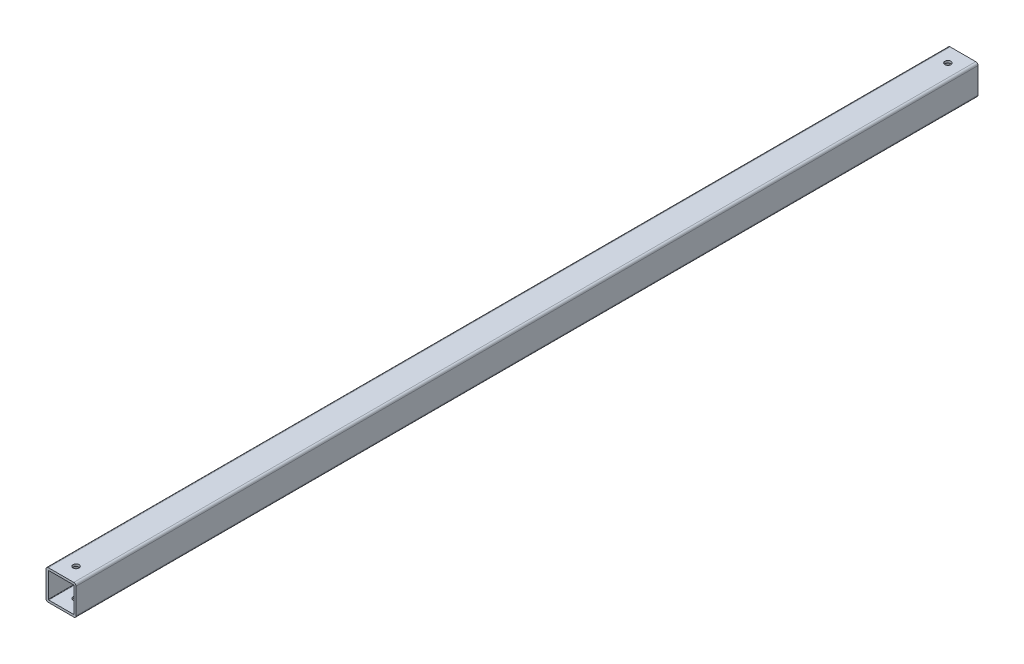
SolidWorks part; units mm, degrees
ref_plane "Front Plane" through (0, 0, 0) normal (0, 0, 1) x (1, 0, 0)
ref_plane "Top Plane" through (0, 0, 0) normal (0, 1, 0) x (1, 0, 0)
ref_plane "Right Plane" through (0, 0, 0) normal (1, 0, 0) x (0, 0, -1)
sketch "Sketch1" plane through (0, 0, 0) normal (0, 0, 1) x (1, 0, 0)
  line L1 (-20, 20) -> (20, 20)
  line L2 (-20, 20) -> (-20, -20)
  line L3 (-20, -20) -> (20, -20)
  line L4 (20, 20) -> (20, -20)
  line L5 (-20, 20) -> (20, -20) construction
  line L6 (-20, -20) -> (20, 20) construction
  point P0 (0, 0)
  dimension "D1" = 40
  dimension "D2" = 40
extrude "Extrude-Thin1" add sketch "Sketch1" along normal blind 1200 thin
fillet "Fillet1" radius 0.5 4 edges at (-17, -17, 600) (-17, 17, 600) (17, 17, 600) (17, -17, 600)
fillet "Fillet2" radius 3 4 edges at (20, -20, 600) (-20, -20, 600) (20, 20, 600) (-20, 20, 600)
hole_wizard "Ø8.0 (8) Diameter Hole1" positions "Sketch4" profile "Sketch3" hole size "Ø8.0" standard "ANSI Metric" end condition through all
sketch "Sketch4" plane through (0, 20, 0) normal (0, 1, 0) x (1, 0, 0)
  line L0 (0, -1200) -> (0, 0) construction
  line L1 (17, -1200) -> (-17, -1200) construction
  point P10 (0, -1180)
  point P12 (0, -20)
  dimension "D1" = 20
  dimension "D2" = 20
sketch "Sketch3" plane through (0, 20, 1180) normal (1, 0, 0) x (0, 0, 1)
  line L0 (0, 0) -> (0, 40)
  line L1 (0, 40) -> (4, 40)
  line L2 (4, 40) -> (4, 0)
  line L5 (4, 0) -> (0, 0)
  line L11 (0, -6.35) -> (0, 107.95) construction
  dimension "Thru Hole Dia." = 8
  dimension "Thru Hole Depth" = 40
equation "\"a\"= \"Beam Profile@Plasma Beta.Assembly\""
equation "\"b\"= 3"
equation "\"L\"= \"Width@Plasma Beta.Assembly\""
equation "\"D2@Sketch1\"=\"a\""
equation "\"D1@Sketch1\"=\"a\""
equation "\"D1@Extrude-Thin1\"=\"L\""
equation "\"D5@Extrude-Thin1\"=\"b\""
equation "\"D1@Fillet2\"=\"b\""
